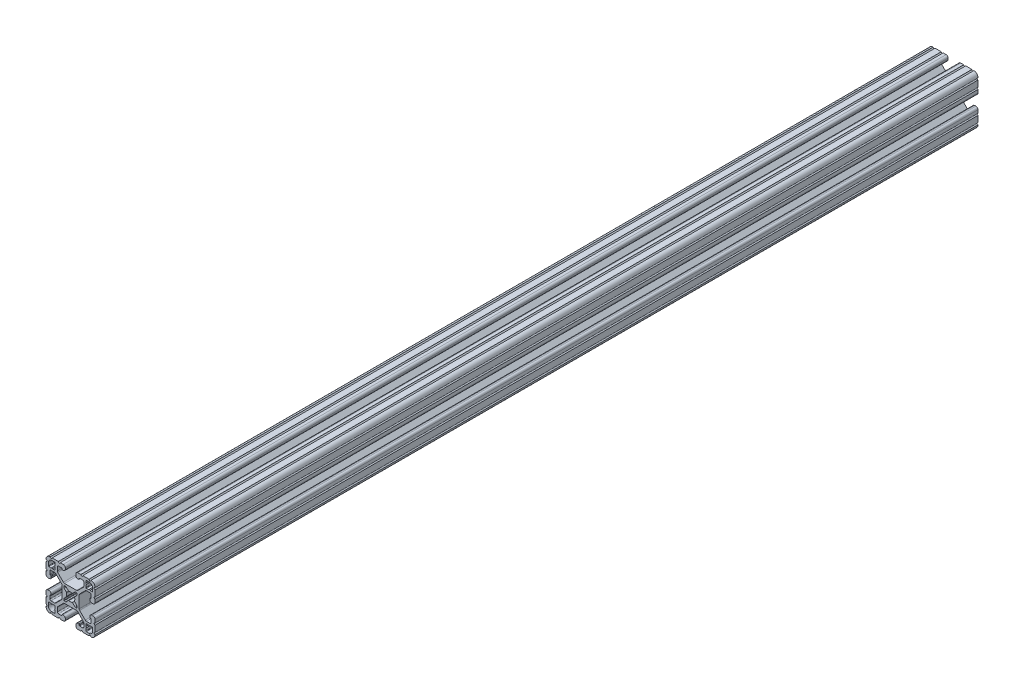
SolidWorks part; units mm, degrees
ref_plane "Front Plane" through (0, 0, 0) normal (0, 0, 1) x (1, 0, 0)
ref_plane "Top Plane" through (0, 0, 0) normal (0, 1, 0) x (1, 0, 0)
ref_plane "Right Plane" through (0, 0, 0) normal (1, 0, 0) x (0, 0, -1)
sketch "Sketch1" plane through (0, 0, 0) normal (0, 0, 1) x (1, 0, 0)
  line L0 (1.5823, 3.1988) -> (3.2921, 4.9085)
  line L1 (3.9207, 5.1689) -> (4.9149, 5.1689)
  line L2 (5.1689, 4.9149) -> (5.1689, 3.9207)
  line L3 (4.9085, 3.2921) -> (3.1988, 1.5823)
  line L4 (3.1988, -1.5823) -> (4.9085, -3.2921)
  line L5 (5.1689, -3.9207) -> (5.1689, -4.9149)
  line L6 (4.9149, -5.1689) -> (3.9207, -5.1689)
  line L7 (3.2921, -4.9085) -> (1.5823, -3.1988)
  line L8 (-1.5823, -3.1988) -> (-3.2921, -4.9085)
  line L9 (-3.9207, -5.1689) -> (-4.9149, -5.1689)
  line L10 (-5.1689, -4.9149) -> (-5.1689, -3.9207)
  line L11 (-4.9085, -3.2921) -> (-3.1988, -1.5823)
  line L12 (-3.1988, 1.5823) -> (-4.9085, 3.2921)
  line L13 (-5.1689, 3.9207) -> (-5.1689, 4.9149)
  line L14 (-4.9149, 5.1689) -> (-3.9207, 5.1689)
  line L15 (-3.2921, 4.9085) -> (-1.5823, 3.1988)
  line L16 (-11.8669, 14.0194) -> (-11.8669, 12.2479)
  line L17 (-12.2479, 11.8669) -> (-14.0195, 11.8669)
  line L18 (-14.0213, 11.8676) -> (-14.5575, 12.4039)
  line L19 (-14.5611, 12.4039) -> (-15.0973, 11.8676)
  line L20 (-15.0991, 11.8669) -> (-16.8707, 11.8669)
  line L21 (-17.2517, 12.2479) -> (-17.2517, 14.4577)
  line L22 (-14.4577, 17.2517) -> (-12.2479, 17.2517)
  line L23 (-11.8669, 16.8707) -> (-11.8669, 15.0991)
  line L24 (-11.8676, 15.0973) -> (-12.4039, 14.5611)
  line L25 (-12.4039, 14.5575) -> (-11.8676, 14.0212)
  line L26 (-14.0194, -11.8669) -> (-12.2479, -11.8669)
  line L27 (-11.8669, -12.2479) -> (-11.8669, -14.0195)
  line L28 (-11.8676, -14.0213) -> (-12.4039, -14.5575)
  line L29 (-12.4039, -14.5611) -> (-11.8676, -15.0973)
  line L30 (-11.8669, -15.0991) -> (-11.8669, -16.8707)
  line L31 (-12.2479, -17.2517) -> (-14.4577, -17.2517)
  line L32 (-17.2517, -14.4577) -> (-17.2517, -12.2479)
  line L33 (-16.8707, -11.8669) -> (-15.0991, -11.8669)
  line L34 (-15.0973, -11.8676) -> (-14.5611, -12.4039)
  line L35 (-14.5575, -12.4039) -> (-14.0212, -11.8676)
  line L36 (11.8669, -14.0194) -> (11.8669, -12.2479)
  line L37 (12.2479, -11.8669) -> (14.0195, -11.8669)
  line L38 (14.0213, -11.8676) -> (14.5575, -12.4039)
  line L39 (14.5611, -12.4039) -> (15.0973, -11.8676)
  line L40 (15.0991, -11.8669) -> (16.8707, -11.8669)
  line L41 (17.2517, -12.2479) -> (17.2517, -14.4577)
  line L42 (14.4577, -17.2517) -> (12.2479, -17.2517)
  line L43 (11.8669, -16.8707) -> (11.8669, -15.0991)
  line L44 (11.8676, -15.0973) -> (12.4039, -14.5611)
  line L45 (12.4039, -14.5575) -> (11.8676, -14.0212)
  line L46 (14.0194, 11.8669) -> (12.2479, 11.8669)
  line L47 (11.8669, 12.2479) -> (11.8669, 14.0195)
  line L48 (11.8676, 14.0213) -> (12.4039, 14.5575)
  line L49 (12.4039, 14.5611) -> (11.8676, 15.0973)
  line L50 (11.8669, 15.0991) -> (11.8669, 16.8707)
  line L51 (12.2479, 17.2517) -> (14.4577, 17.2517)
  line L52 (17.2517, 14.4577) -> (17.2517, 12.2479)
  line L53 (16.8707, 11.8669) -> (15.0991, 11.8669)
  line L54 (15.0973, 11.8676) -> (14.5611, 12.4039)
  line L55 (14.5575, 12.4039) -> (14.0212, 11.8676)
  line L56 (6.3498, -14.9848) -> (5.6531, -14.9848)
  line L57 (4.0778, -16.5601) -> (4.0778, -17.4747)
  line L58 (5.6531, -19.05) -> (7.9756, -19.05)
  line L59 (9.4996, -19.05) -> (14.2981, -19.05)
  line L60 (19.05, -14.3256) -> (19.05, -9.4996)
  line L61 (19.05, -7.9756) -> (19.05, -5.6531)
  line L62 (17.4747, -4.0778) -> (16.5601, -4.0778)
  line L63 (14.9848, -5.6531) -> (14.9848, -6.3498)
  line L64 (15.3661, -6.731) -> (15.6969, -6.731)
  line L65 (16.0782, -7.1122) -> (16.0782, -9.3968)
  line L66 (15.1881, -10.287) -> (12.3526, -10.2871)
  line L67 (11.4535, -9.9142) -> (7.1147, -5.5659)
  line L68 (6.7437, -4.6689) -> (6.7437, 4.6414)
  line L69 (7.1147, 5.5384) -> (11.481, 9.9142)
  line L70 (12.38, 10.2871) -> (15.1881, 10.287)
  line L71 (16.0782, 9.3968) -> (16.0782, 7.1122)
  line L72 (15.6969, 6.731) -> (15.3661, 6.731)
  line L73 (14.9848, 6.3498) -> (14.9848, 5.6531)
  line L74 (16.5601, 4.0778) -> (17.4747, 4.0778)
  line L75 (19.05, 5.6531) -> (19.05, 7.9756)
  line L76 (19.05, 9.4996) -> (19.05, 14.2981)
  line L77 (14.3256, 19.05) -> (9.4996, 19.05)
  line L78 (7.9756, 19.05) -> (5.6531, 19.05)
  line L79 (4.0778, 17.4747) -> (4.0778, 16.5601)
  line L80 (5.6531, 14.9848) -> (6.3498, 14.9848)
  line L81 (6.731, 15.3661) -> (6.731, 15.6969)
  line L82 (7.1122, 16.0782) -> (9.3968, 16.0782)
  line L83 (10.287, 15.1881) -> (10.2871, 12.3526)
  line L84 (9.9142, 11.4535) -> (5.5659, 7.1147)
  line L85 (4.6689, 6.7437) -> (-4.6414, 6.7437)
  line L86 (-5.5384, 7.1147) -> (-9.9142, 11.481)
  line L87 (-10.2871, 12.38) -> (-10.287, 15.1881)
  line L88 (-9.3968, 16.0782) -> (-7.1122, 16.0782)
  line L89 (-6.731, 15.6969) -> (-6.731, 15.3661)
  line L90 (-6.3498, 14.9848) -> (-5.6531, 14.9848)
  line L91 (-4.0778, 16.5601) -> (-4.0778, 17.4747)
  line L92 (-5.6531, 19.05) -> (-7.9756, 19.05)
  line L93 (-9.4996, 19.05) -> (-14.2981, 19.05)
  line L94 (-19.05, 14.3256) -> (-19.05, 9.4996)
  line L95 (-19.05, 7.9756) -> (-19.05, 5.6531)
  line L96 (-17.4747, 4.0778) -> (-16.5601, 4.0778)
  line L97 (-14.9848, 5.6531) -> (-14.9848, 6.3498)
  line L98 (-15.3661, 6.731) -> (-15.6969, 6.731)
  line L99 (-16.0782, 7.1122) -> (-16.0782, 9.3968)
  line L100 (-15.1881, 10.287) -> (-12.3526, 10.2871)
  line L101 (-11.4535, 9.9142) -> (-7.1147, 5.5659)
  line L102 (-6.7437, 4.6689) -> (-6.7437, -4.6414)
  line L103 (-7.1147, -5.5384) -> (-11.481, -9.9142)
  line L104 (-12.38, -10.2871) -> (-15.1881, -10.287)
  line L105 (-16.0782, -9.3968) -> (-16.0782, -7.1122)
  line L106 (-15.6969, -6.731) -> (-15.3661, -6.731)
  line L107 (-14.9848, -6.3498) -> (-14.9848, -5.6531)
  line L108 (-16.5601, -4.0778) -> (-17.4747, -4.0778)
  line L109 (-19.05, -5.6531) -> (-19.05, -7.9756)
  line L110 (-19.05, -9.4996) -> (-19.05, -14.2981)
  line L111 (-14.3256, -19.05) -> (-9.4996, -19.05)
  line L112 (-7.9756, -19.05) -> (-5.6531, -19.05)
  line L113 (-4.0778, -17.4747) -> (-4.0778, -16.5601)
  line L114 (-5.6531, -14.9848) -> (-6.3498, -14.9848)
  line L115 (-6.731, -15.3661) -> (-6.731, -15.6969)
  line L116 (-7.1122, -16.0782) -> (-9.3968, -16.0782)
  line L117 (-10.287, -15.1881) -> (-10.2871, -12.3526)
  line L118 (-9.9142, -11.4535) -> (-5.5659, -7.1147)
  line L119 (-4.6689, -6.7437) -> (4.6414, -6.7437)
  line L120 (5.5384, -7.1147) -> (9.9142, -11.481)
  line L121 (10.2871, -12.38) -> (10.287, -15.1881)
  line L122 (9.3968, -16.0782) -> (7.1122, -16.0782)
  line L123 (6.731, -15.6969) -> (6.731, -15.3661)
  arc A0 (1.178, 3.1119) -> (1.5823, 3.1988) centre (1.3129, 3.4682) ccw
  arc A1 (3.9207, 5.1689) -> (3.2921, 4.9085) centre (3.9207, 4.2799) ccw
  arc A2 (5.1689, 4.9149) -> (4.9149, 5.1689) centre (4.9149, 4.9149) ccw
  arc A3 (4.9085, 3.2921) -> (5.1689, 3.9207) centre (4.2799, 3.9207) ccw
  arc A4 (3.1988, 1.5823) -> (3.1119, 1.178) centre (3.4682, 1.3129) ccw
  arc A5 (3.1119, -1.178) -> (3.1119, 1.178) centre (0, 0) ccw
  arc A6 (3.1119, -1.178) -> (3.1988, -1.5823) centre (3.4682, -1.3129) ccw
  arc A7 (5.1689, -3.9207) -> (4.9085, -3.2921) centre (4.2799, -3.9207) ccw
  arc A8 (4.9149, -5.1689) -> (5.1689, -4.9149) centre (4.9149, -4.9149) ccw
  arc A9 (3.2921, -4.9085) -> (3.9207, -5.1689) centre (3.9207, -4.2799) ccw
  arc A10 (1.5823, -3.1988) -> (1.178, -3.1119) centre (1.3129, -3.4682) ccw
  arc A11 (-1.178, -3.1119) -> (1.178, -3.1119) centre (0, 0) ccw
  arc A12 (-1.178, -3.1119) -> (-1.5823, -3.1988) centre (-1.3129, -3.4682) ccw
  arc A13 (-3.9207, -5.1689) -> (-3.2921, -4.9085) centre (-3.9207, -4.2799) ccw
  arc A14 (-5.1689, -4.9149) -> (-4.9149, -5.1689) centre (-4.9149, -4.9149) ccw
  arc A15 (-4.9085, -3.2921) -> (-5.1689, -3.9207) centre (-4.2799, -3.9207) ccw
  arc A16 (-3.1988, -1.5823) -> (-3.1119, -1.178) centre (-3.4682, -1.3129) ccw
  arc A17 (-3.1119, 1.178) -> (-3.1119, -1.178) centre (0, 0) ccw
  arc A18 (-3.1119, 1.178) -> (-3.1988, 1.5823) centre (-3.4682, 1.3129) ccw
  arc A19 (-5.1689, 3.9207) -> (-4.9085, 3.2921) centre (-4.2799, 3.9207) ccw
  arc A20 (-4.9149, 5.1689) -> (-5.1689, 4.9149) centre (-4.9149, 4.9149) ccw
  arc A21 (-3.2921, 4.9085) -> (-3.9207, 5.1689) centre (-3.9207, 4.2799) ccw
  arc A22 (-1.5823, 3.1988) -> (-1.178, 3.1119) centre (-1.3129, 3.4682) ccw
  arc A23 (1.178, 3.1119) -> (-1.178, 3.1119) centre (0, 0) ccw
  arc A24 (-11.8669, 14.0194) -> (-11.8676, 14.0212) centre (-11.8694, 14.0194) ccw
  arc A25 (-12.2479, 11.8669) -> (-11.8669, 12.2479) centre (-12.2479, 12.2479) ccw
  arc A26 (-14.0213, 11.8676) -> (-14.0195, 11.8669) centre (-14.0195, 11.8694) ccw
  arc A27 (-14.5575, 12.4039) -> (-14.5611, 12.4039) centre (-14.5593, 12.4021) ccw
  arc A28 (-15.0991, 11.8669) -> (-15.0973, 11.8676) centre (-15.0991, 11.8694) ccw
  arc A29 (-17.2517, 12.2479) -> (-16.8707, 11.8669) centre (-16.8707, 12.2479) ccw
  arc A30 (-14.4577, 17.2517) -> (-17.2517, 14.4577) centre (-14.4577, 14.4577) ccw
  arc A31 (-11.8669, 16.8707) -> (-12.2479, 17.2517) centre (-12.2479, 16.8707) ccw
  arc A32 (-11.8676, 15.0973) -> (-11.8669, 15.0991) centre (-11.8694, 15.0991) ccw
  arc A33 (-12.4039, 14.5611) -> (-12.4039, 14.5575) centre (-12.4021, 14.5593) ccw
  arc A34 (-14.0194, -11.8669) -> (-14.0212, -11.8676) centre (-14.0194, -11.8694) ccw
  arc A35 (-11.8669, -12.2479) -> (-12.2479, -11.8669) centre (-12.2479, -12.2479) ccw
  arc A36 (-11.8676, -14.0213) -> (-11.8669, -14.0195) centre (-11.8694, -14.0195) ccw
  arc A37 (-12.4039, -14.5575) -> (-12.4039, -14.5611) centre (-12.4021, -14.5593) ccw
  arc A38 (-11.8669, -15.0991) -> (-11.8676, -15.0973) centre (-11.8694, -15.0991) ccw
  arc A39 (-12.2479, -17.2517) -> (-11.8669, -16.8707) centre (-12.2479, -16.8707) ccw
  arc A40 (-17.2517, -14.4577) -> (-14.4577, -17.2517) centre (-14.4577, -14.4577) ccw
  arc A41 (-16.8707, -11.8669) -> (-17.2517, -12.2479) centre (-16.8707, -12.2479) ccw
  arc A42 (-15.0973, -11.8676) -> (-15.0991, -11.8669) centre (-15.0991, -11.8694) ccw
  arc A43 (-14.5611, -12.4039) -> (-14.5575, -12.4039) centre (-14.5593, -12.4021) ccw
  arc A44 (11.8669, -14.0194) -> (11.8676, -14.0212) centre (11.8694, -14.0194) ccw
  arc A45 (12.2479, -11.8669) -> (11.8669, -12.2479) centre (12.2479, -12.2479) ccw
  arc A46 (14.0213, -11.8676) -> (14.0195, -11.8669) centre (14.0195, -11.8694) ccw
  arc A47 (14.5575, -12.4039) -> (14.5611, -12.4039) centre (14.5593, -12.4021) ccw
  arc A48 (15.0991, -11.8669) -> (15.0973, -11.8676) centre (15.0991, -11.8694) ccw
  arc A49 (17.2517, -12.2479) -> (16.8707, -11.8669) centre (16.8707, -12.2479) ccw
  arc A50 (14.4577, -17.2517) -> (17.2517, -14.4577) centre (14.4577, -14.4577) ccw
  arc A51 (11.8669, -16.8707) -> (12.2479, -17.2517) centre (12.2479, -16.8707) ccw
  arc A52 (11.8676, -15.0973) -> (11.8669, -15.0991) centre (11.8694, -15.0991) ccw
  arc A53 (12.4039, -14.5611) -> (12.4039, -14.5575) centre (12.4021, -14.5593) ccw
  arc A54 (14.0194, 11.8669) -> (14.0212, 11.8676) centre (14.0194, 11.8694) ccw
  arc A55 (11.8669, 12.2479) -> (12.2479, 11.8669) centre (12.2479, 12.2479) ccw
  arc A56 (11.8676, 14.0213) -> (11.8669, 14.0195) centre (11.8694, 14.0195) ccw
  arc A57 (12.4039, 14.5575) -> (12.4039, 14.5611) centre (12.4021, 14.5593) ccw
  arc A58 (11.8669, 15.0991) -> (11.8676, 15.0973) centre (11.8694, 15.0991) ccw
  arc A59 (12.2479, 17.2517) -> (11.8669, 16.8707) centre (12.2479, 16.8707) ccw
  arc A60 (17.2517, 14.4577) -> (14.4577, 17.2517) centre (14.4577, 14.4577) ccw
  arc A61 (16.8707, 11.8669) -> (17.2517, 12.2479) centre (16.8707, 12.2479) ccw
  arc A62 (15.0973, 11.8676) -> (15.0991, 11.8669) centre (15.0991, 11.8694) ccw
  arc A63 (14.5611, 12.4039) -> (14.5575, 12.4039) centre (14.5593, 12.4021) ccw
  arc A64 (6.731, -15.3661) -> (6.3498, -14.9848) centre (6.35, -15.3658) ccw
  arc A65 (5.6531, -14.9848) -> (4.0778, -16.5601) centre (5.6526, -16.5596) ccw
  arc A66 (4.0778, -17.4747) -> (5.6531, -19.05) centre (5.6526, -17.4752) ccw
  arc A67 (9.4996, -19.05) -> (7.9756, -19.05) centre (8.7376, -19.05) ccw
  arc A68 (15.8221, -19.0496) -> (14.2981, -19.05) centre (15.0601, -19.05) ccw
  arc A69 (15.8221, -19.0496) -> (19.0499, -15.8496) centre (15.875, -15.875) ccw
  arc A70 (19.05, -14.3256) -> (19.0499, -15.8496) centre (19.05, -15.0876) ccw
  arc A71 (19.05, -7.9756) -> (19.05, -9.4996) centre (19.05, -8.7376) ccw
  arc A72 (19.05, -5.6531) -> (17.4747, -4.0778) centre (17.4752, -5.6526) ccw
  arc A73 (16.5601, -4.0778) -> (14.9848, -5.6531) centre (16.5596, -5.6526) ccw
  arc A74 (14.9848, -6.3498) -> (15.3661, -6.731) centre (15.3658, -6.35) ccw
  arc A75 (16.0782, -7.1122) -> (15.6969, -6.731) centre (15.6972, -7.112) ccw
  arc A76 (15.1881, -10.287) -> (16.0782, -9.3968) centre (15.1892, -9.398) ccw
  arc A77 (11.4535, -9.9142) -> (12.3526, -10.2871) centre (12.3525, -9.0171) ccw
  arc A78 (6.7437, -4.6689) -> (7.1147, -5.5659) centre (8.0137, -4.6689) ccw
  arc A79 (7.1147, 5.5384) -> (6.7437, 4.6414) centre (8.0137, 4.6414) ccw
  arc A80 (12.38, 10.2871) -> (11.481, 9.9142) centre (12.38, 9.0171) ccw
  arc A81 (16.0782, 9.3968) -> (15.1881, 10.287) centre (15.1892, 9.398) ccw
  arc A82 (15.6969, 6.731) -> (16.0782, 7.1122) centre (15.6972, 7.112) ccw
  arc A83 (15.3661, 6.731) -> (14.9848, 6.3498) centre (15.3658, 6.35) ccw
  arc A84 (14.9848, 5.6531) -> (16.5601, 4.0778) centre (16.5596, 5.6526) ccw
  arc A85 (17.4747, 4.0778) -> (19.05, 5.6531) centre (17.4752, 5.6526) ccw
  arc A86 (19.05, 9.4996) -> (19.05, 7.9756) centre (19.05, 8.7376) ccw
  arc A87 (19.0496, 15.8221) -> (19.05, 14.2981) centre (19.05, 15.0601) ccw
  arc A88 (19.0496, 15.8221) -> (15.8496, 19.0499) centre (15.875, 15.875) ccw
  arc A89 (14.3256, 19.05) -> (15.8496, 19.0499) centre (15.0876, 19.05) ccw
  arc A90 (7.9756, 19.05) -> (9.4996, 19.05) centre (8.7376, 19.05) ccw
  arc A91 (5.6531, 19.05) -> (4.0778, 17.4747) centre (5.6526, 17.4752) ccw
  arc A92 (4.0778, 16.5601) -> (5.6531, 14.9848) centre (5.6526, 16.5596) ccw
  arc A93 (6.3498, 14.9848) -> (6.731, 15.3661) centre (6.35, 15.3658) ccw
  arc A94 (7.1122, 16.0782) -> (6.731, 15.6969) centre (7.112, 15.6972) ccw
  arc A95 (10.287, 15.1881) -> (9.3968, 16.0782) centre (9.398, 15.1892) ccw
  arc A96 (9.9142, 11.4535) -> (10.2871, 12.3526) centre (9.0171, 12.3525) ccw
  arc A97 (4.6689, 6.7437) -> (5.5659, 7.1147) centre (4.6689, 8.0137) ccw
  arc A98 (-5.5384, 7.1147) -> (-4.6414, 6.7437) centre (-4.6414, 8.0137) ccw
  arc A99 (-10.2871, 12.38) -> (-9.9142, 11.481) centre (-9.0171, 12.38) ccw
  arc A100 (-9.3968, 16.0782) -> (-10.287, 15.1881) centre (-9.398, 15.1892) ccw
  arc A101 (-6.731, 15.6969) -> (-7.1122, 16.0782) centre (-7.112, 15.6972) ccw
  arc A102 (-6.731, 15.3661) -> (-6.3498, 14.9848) centre (-6.35, 15.3658) ccw
  arc A103 (-5.6531, 14.9848) -> (-4.0778, 16.5601) centre (-5.6526, 16.5596) ccw
  arc A104 (-4.0778, 17.4747) -> (-5.6531, 19.05) centre (-5.6526, 17.4752) ccw
  arc A105 (-9.4996, 19.05) -> (-7.9756, 19.05) centre (-8.7376, 19.05) ccw
  arc A106 (-15.8221, 19.0496) -> (-14.2981, 19.05) centre (-15.0601, 19.05) ccw
  arc A107 (-15.8221, 19.0496) -> (-19.0499, 15.8496) centre (-15.875, 15.875) ccw
  arc A108 (-19.05, 14.3256) -> (-19.0499, 15.8496) centre (-19.05, 15.0876) ccw
  arc A109 (-19.05, 7.9756) -> (-19.05, 9.4996) centre (-19.05, 8.7376) ccw
  arc A110 (-19.05, 5.6531) -> (-17.4747, 4.0778) centre (-17.4752, 5.6526) ccw
  arc A111 (-16.5601, 4.0778) -> (-14.9848, 5.6531) centre (-16.5596, 5.6526) ccw
  arc A112 (-14.9848, 6.3498) -> (-15.3661, 6.731) centre (-15.3658, 6.35) ccw
  arc A113 (-16.0782, 7.1122) -> (-15.6969, 6.731) centre (-15.6972, 7.112) ccw
  arc A114 (-15.1881, 10.287) -> (-16.0782, 9.3968) centre (-15.1892, 9.398) ccw
  arc A115 (-11.4535, 9.9142) -> (-12.3526, 10.2871) centre (-12.3525, 9.0171) ccw
  arc A116 (-6.7437, 4.6689) -> (-7.1147, 5.5659) centre (-8.0137, 4.6689) ccw
  arc A117 (-7.1147, -5.5384) -> (-6.7437, -4.6414) centre (-8.0137, -4.6414) ccw
  arc A118 (-12.38, -10.2871) -> (-11.481, -9.9142) centre (-12.38, -9.0171) ccw
  arc A119 (-16.0782, -9.3968) -> (-15.1881, -10.287) centre (-15.1892, -9.398) ccw
  arc A120 (-15.6969, -6.731) -> (-16.0782, -7.1122) centre (-15.6972, -7.112) ccw
  arc A121 (-15.3661, -6.731) -> (-14.9848, -6.3498) centre (-15.3658, -6.35) ccw
  arc A122 (-14.9848, -5.6531) -> (-16.5601, -4.0778) centre (-16.5596, -5.6526) ccw
  arc A123 (-17.4747, -4.0778) -> (-19.05, -5.6531) centre (-17.4752, -5.6526) ccw
  arc A124 (-19.05, -9.4996) -> (-19.05, -7.9756) centre (-19.05, -8.7376) ccw
  arc A125 (-19.0496, -15.8221) -> (-19.05, -14.2981) centre (-19.05, -15.0601) ccw
  arc A126 (-19.0496, -15.8221) -> (-15.8496, -19.0499) centre (-15.875, -15.875) ccw
  arc A127 (-14.3256, -19.05) -> (-15.8496, -19.0499) centre (-15.0876, -19.05) ccw
  arc A128 (-7.9756, -19.05) -> (-9.4996, -19.05) centre (-8.7376, -19.05) ccw
  arc A129 (-5.6531, -19.05) -> (-4.0778, -17.4747) centre (-5.6526, -17.4752) ccw
  arc A130 (-4.0778, -16.5601) -> (-5.6531, -14.9848) centre (-5.6526, -16.5596) ccw
  arc A131 (-6.3498, -14.9848) -> (-6.731, -15.3661) centre (-6.35, -15.3658) ccw
  arc A132 (-7.1122, -16.0782) -> (-6.731, -15.6969) centre (-7.112, -15.6972) ccw
  arc A133 (-10.287, -15.1881) -> (-9.3968, -16.0782) centre (-9.398, -15.1892) ccw
  arc A134 (-9.9142, -11.4535) -> (-10.2871, -12.3526) centre (-9.0171, -12.3525) ccw
  arc A135 (-4.6689, -6.7437) -> (-5.5659, -7.1147) centre (-4.6689, -8.0137) ccw
  arc A136 (5.5384, -7.1147) -> (4.6414, -6.7437) centre (4.6414, -8.0137) ccw
  arc A137 (10.2871, -12.38) -> (9.9142, -11.481) centre (9.0171, -12.38) ccw
  arc A138 (9.3968, -16.0782) -> (10.287, -15.1881) centre (9.398, -15.1892) ccw
  arc A139 (6.731, -15.6969) -> (7.1122, -16.0782) centre (7.112, -15.6972) ccw
extrude "Extrude1" add sketch "Sketch1" against normal blind 685.8
